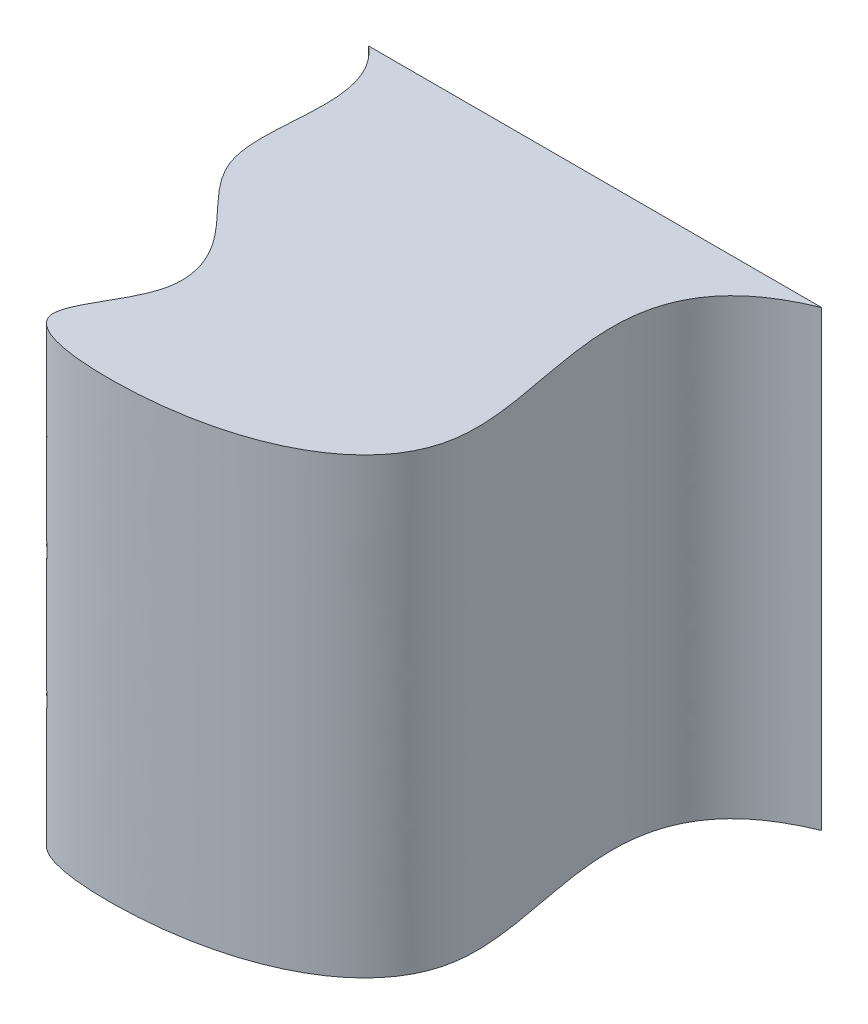
SolidWorks part; units mm, degrees
ref_plane "Front Plane" through (0, 0, 0) normal (0, 0, 1) x (1, 0, 0)
ref_plane "Top Plane" through (0, 0, 0) normal (0, 1, 0) x (1, 0, 0)
ref_plane "Right Plane" through (0, 0, 0) normal (1, 0, 0) x (0, 0, -1)
sketch "Sketch1" plane through (0, 0, 0) normal (0, 0, 1) x (1, 0, 0)
  line L1 (0, 0) -> (300, 0)
  line L2 (0, 0) -> (0, 300)
  line L3 (0, 300) -> (300, 300)
  line L4 (300, 0) -> (300, 300)
  dimension "D1" = 300
  dimension "D2" = 300
extrude "Boss-Extrude2" add sketch "Sketch1" along normal blind 300
sketch "Sketch3" plane through (0, 300, 0) normal (0, 1, 0) x (1, 0, 0)
  line L0 (0, 0) -> (0, -300)
  line L1 (0, -300) -> (300, -300)
  line L2 (300, -300) -> (300, 0)
  spline S0 degree 3 poles (0, 0) (35.165, -29.6523) (-8.3577, -109.6255) (63.8759, -155.9944) (80.1316, -212.4077) (23.7939, -271.0059) (158.6832, -285.5151) (321.4675, -212.4554) (194.6017, -42.9835) (300, 0) knots 0 0 0 0 0.161035 0.258683 0.309274 0.391817 0.481289 0.701541 1 1 1 1
extrude "Cut-Extrude2" cut sketch "Sketch3" against normal blind 300
